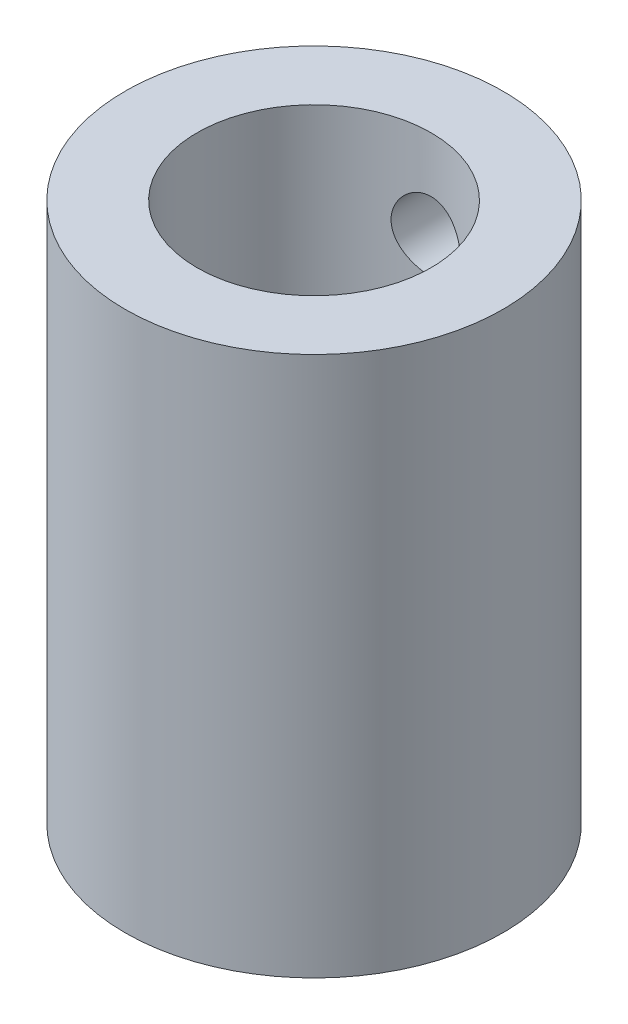
SolidWorks part; units mm, degrees
ref_plane "Plan de face" through (0, 0, 0) normal (0, 0, 1) x (1, 0, 0)
ref_plane "Plan de dessus" through (0, 0, 0) normal (0, 1, 0) x (1, 0, 0)
ref_plane "Plan de droite" through (0, 0, 0) normal (1, 0, 0) x (0, 0, -1)
sketch "Esquisse1" plane through (0, 0, 0) normal (0, 1, 0) x (1, 0, 0)
  circle A0 centre (0, 0) radius 3.25
  circle A1 centre (0, 0) radius 5.25
  dimension "D1" = 6.5
  dimension "D2" = 2
extrude "BASE" add sketch "Esquisse1" along normal blind 15
sketch "Esquisse2" plane through (0, 0, 0) normal (0, 0, 1) x (1, 0, 0)
  line L0 (5.25, 15) -> (-5.25, 15) construction
  line L1 (5.25, 0) -> (-5.25, 15) construction
  line L2 (-5.25, 15) -> (-5.25, 7.5) construction
  line L3 (-5.25, 7.5) -> (5.25, 7.5) construction
  line L4 (5.25, 0) -> (5.25, 15) construction
  line L5 (5.25, 7.5) -> (0, 15) construction
  line L6 (0, 15) -> (0, 7.5) construction
  circle A0 centre (0, 12.5) radius 0.9648
  dimension "D1" = 2.5
extrude "VIDE GOUPILLE" cut sketch "Esquisse2" against normal up to surface (5.1606 mm away)
